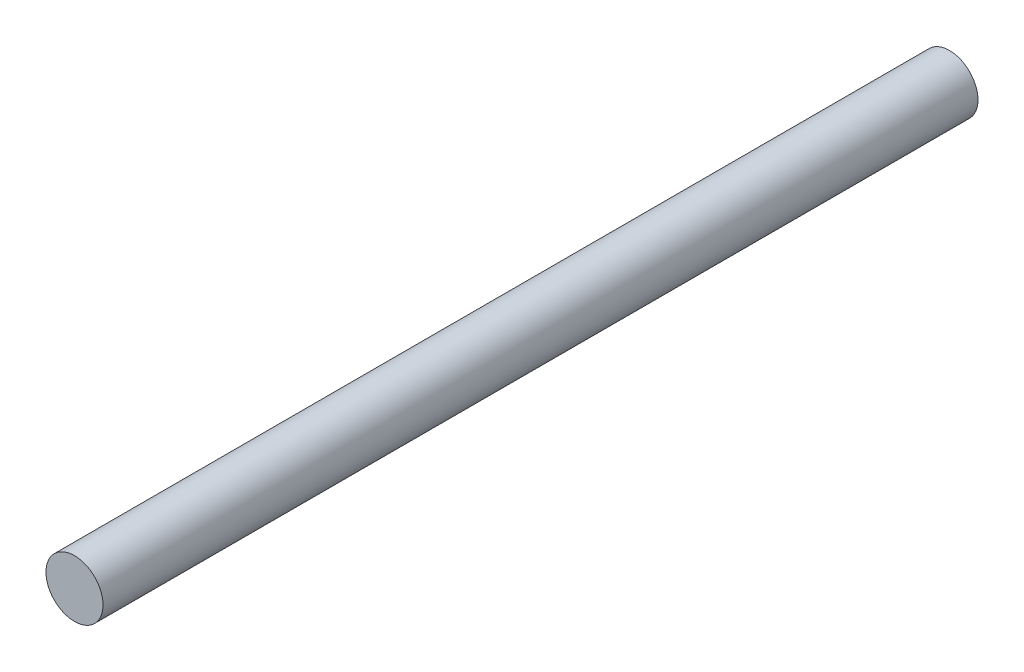
SolidWorks part; units mm, degrees
ref_plane "Alzado" through (0, 0, 0) normal (0, 0, 1) x (1, 0, 0)
ref_plane "Planta" through (0, 0, 0) normal (0, 1, 0) x (1, 0, 0)
ref_plane "Vista lateral" through (0, 0, 0) normal (1, 0, 0) x (0, 0, -1)
sketch "Croquis1" plane through (0, 0, 0) normal (0, 0, 1) x (1, 0, 0)
  circle A0 centre (0, 0) radius 1.5
  dimension "D1" = 3
extrude "Saliente-Extruir1" add sketch "Croquis1" along normal blind 46
